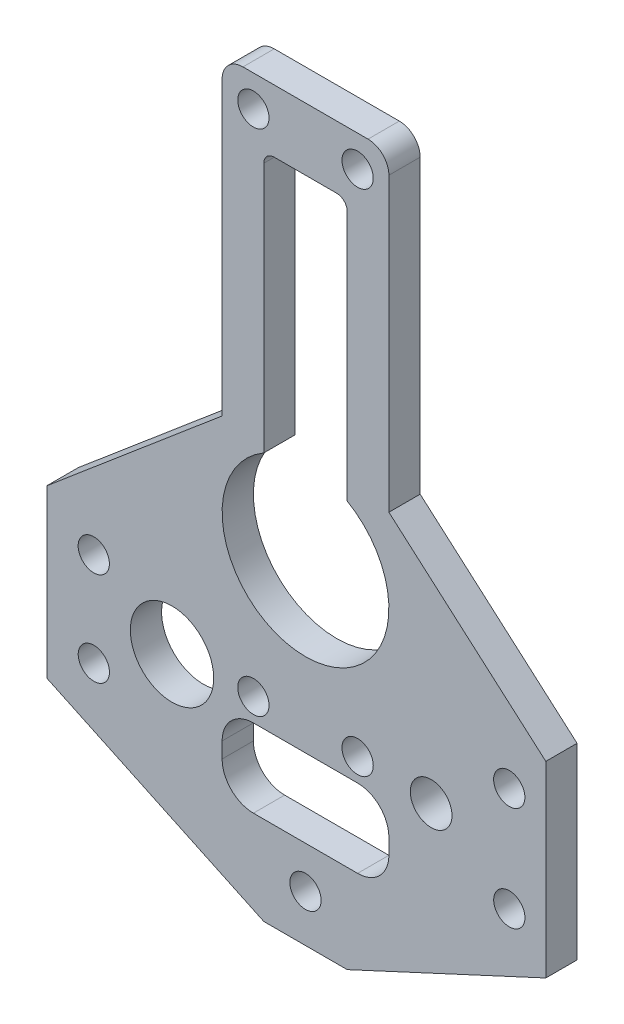
SolidWorks part; units mm, degrees
material "Cast Stainless Steel"
ref_plane "Front Plane" through (0, 0, 0) normal (0, 0, 1) x (1, 0, 0)
ref_plane "Top Plane" through (0, 0, 0) normal (0, 1, 0) x (1, 0, 0)
ref_plane "Right Plane" through (0, 0, 0) normal (1, 0, 0) x (0, 0, -1)
sketch "Sketch1" plane through (0, 0, 0) normal (0, 0, 1) x (1, 0, 0)
  line L0 (0, 70) -> (0, -70) construction
  line L1 (-6, 70) -> (6, 70)
  line L2 (-4, 0) -> (4, 0)
  line L3 (8, 68) -> (8, 40)
  line L4 (8, 40) -> (23.0528, 26.8313)
  line L5 (23.0528, 26.8313) -> (23.0528, 8.8313)
  line L6 (23.0528, 8.8313) -> (4, 0)
  line L7 (-4, 0) -> (-24.8062, 9.8031)
  line L8 (-24.8062, 9.8031) -> (-24.8062, 25.8031)
  line L9 (-24.8062, 25.8031) -> (-8, 40)
  line L10 (-8, 40) -> (-8, 68)
  line L11 (-3, 64) -> (3, 64)
  line L12 (-4, 63) -> (-4, 38.9282)
  line L13 (4, 63) -> (4, 38.9282)
  line L14 (-24.8062, 17.8031) -> (23.0528, 17.8313) construction
  line L15 (-5, 16) -> (5, 16)
  line L16 (-8, 13) -> (-8, 11.5)
  line L17 (-5, 8.5) -> (5, 8.5)
  line L18 (8, 13) -> (8, 11.5)
  line L19 (-8, 16) -> (8, 8.5) construction
  line L20 (-8, 8.5) -> (8, 16) construction
  line L21 (-8, 42.6) -> (8, 42.6) construction
  arc A0 (-4, 38.9282) -> (4, 38.9282) centre (0, 32) ccw
  circle A1 centre (0, 4.5) radius 1.5
  circle A2 centre (-20.3062, 13.3031) radius 1.5
  circle A3 centre (-20.3115, 22.3084) radius 1.5
  circle A4 centre (-12.8062, 17.8102) radius 4
  arc A5 (-8, 11.5) -> (-5, 8.5) centre (-5, 11.5) ccw
  arc A6 (5, 8.5) -> (8, 11.5) centre (5, 11.5) ccw
  arc A7 (5, 16) -> (8, 13) centre (5, 13) cw
  arc A8 (-5, 16) -> (-8, 13) centre (-5, 13) ccw
  arc A9 (6, 70) -> (8, 68) centre (6, 68) cw
  arc A10 (-6, 70) -> (-8, 68) centre (-6, 68) ccw
  arc A11 (4, 38.9282) -> (0, 40) centre (0, 32) ccw construction
  arc A12 (0, 40) -> (-4, 38.9282) centre (0, 32) ccw construction
  circle A13 centre (-5, 67) radius 1.5
  circle A14 centre (5, 67) radius 1.5
  circle A15 centre (5, 18.2) radius 1.5
  circle A16 centre (-5, 18.2) radius 1.5
  circle A17 centre (19.5528, 12.8293) radius 1.5
  circle A18 centre (19.5469, 22.8293) radius 1.5
  circle A19 centre (12.0528, 17.8248) radius 2
  arc A20 (3, 64) -> (4, 63) centre (3, 63) cw
  arc A21 (-3, 64) -> (-4, 63) centre (-3, 63) ccw
  point P4 (0, 0)
  point P8 (0, 70)
  point P11 (0, 0)
  point P20 (0, 64)
  point P22 (4, 50.9641)
  point P24 (0, 12.25)
  point P32 (-24.8062, 17.8031)
  point P54 (8, 70)
  point P57 (-8, 70)
  dimension "D13" = 16
  dimension "D19" = 3
  dimension "D21" = 3
  dimension "D25" = 8
  dimension "D26" = 3
  dimension "D27" = 2
  dimension "D30" = 3
  dimension "D33" = 3
  dimension "D35" = 4
  dimension "D37" = 1
  dimension "D1" = 16
  dimension "D2" = 8
  dimension "D3" = 70
  dimension "D4" = 21
  dimension "D5" = 18
  dimension "D6" = 30
  dimension "D7" = 20
  dimension "D8" = 16
  dimension "D9" = 23
  dimension "D10" = 22
  dimension "D11" = 30
  dimension "D12" = 6
  dimension "D14" = 32
  dimension "D15" = 8
  dimension "D16" = 16
  dimension "D17" = 16
  dimension "D18" = 7.5
  dimension "D20" = 4.5
  dimension "D22" = 4.5
  dimension "D23" = 3.5
  dimension "D24" = 12
  dimension "D28" = 5
  dimension "D29" = 3
  dimension "D31" = 24.4
  dimension "D32" = 3.5
  dimension "D34" = 5
  dimension "D36" = 11
extrude "Boss-Extrude1" add sketch "Sketch1" along normal blind 3
